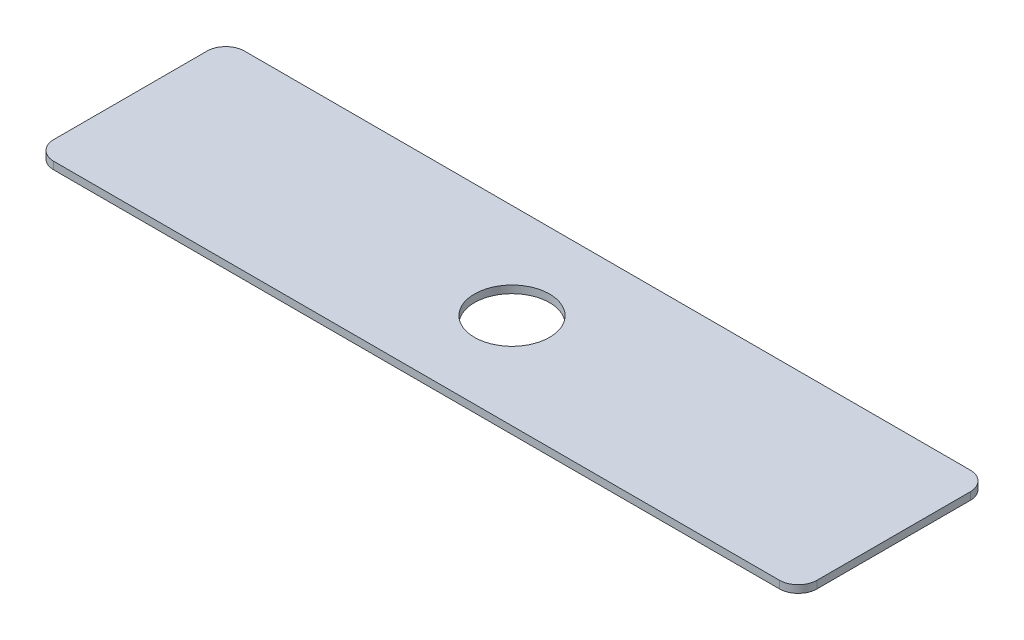
SolidWorks part; units mm, degrees
ref_plane "Front Plane" through (0, 0, 0) normal (0, 0, 1) x (1, 0, 0)
ref_plane "Top Plane" through (0, 0, 0) normal (0, 1, 0) x (1, 0, 0)
ref_plane "Right Plane" through (0, 0, 0) normal (1, 0, 0) x (0, 0, -1)
sketch "Sketch2" plane through (0, 0, 0) normal (0, 1, 0) x (1, 0, 0)
  line L1 (-101.6, 25.4) -> (101.6, 25.4)
  line L2 (-101.6, 25.4) -> (-101.6, -25.4)
  line L3 (-101.6, -25.4) -> (101.6, -25.4)
  line L4 (101.6, 25.4) -> (101.6, -25.4)
  line L5 (-101.6, 25.4) -> (101.6, -25.4) construction
  line L6 (-101.6, -25.4) -> (101.6, 25.4) construction
  point P0 (0, 0)
  dimension "D1" = 203.2
  dimension "D2" = 50.8
extrude "Boss-Extrude1" add sketch "Sketch2" along normal mid plane 2
fillet "Fillet1" radius 5 4 edges at (-101.6, 0, 25.4) (-101.6, 0, -25.4) (101.6, 0, -25.4) (101.6, 0, 25.4)
sketch "Sketch3" plane through (0, 0, 0) normal (0, 1, 0) x (1, 0, 0)
  circle A0 centre (0, 0) radius 10
  dimension "D1" = 20
extrude "Cut-Extrude1" cut sketch "Sketch3" against normal through all both and the other way through all
equation "\"Width\"= 8in"
equation "\"Height\"= 2in"
equation "\"Thick\"= 2mm"
equation "\"Fillet\"= 5mm"
equation "\"D1@Sketch2\"=\"Width\""
equation "\"D2@Sketch2\"=\"Height\""
equation "\"D1@Boss-Extrude1\"=\"Thick\""
equation "\"D1@Fillet1\"=\"Fillet\""
equation "\"CenterPivot\" = 20mm"
equation "\"D1@Sketch3\"=\"CenterPivot\""
